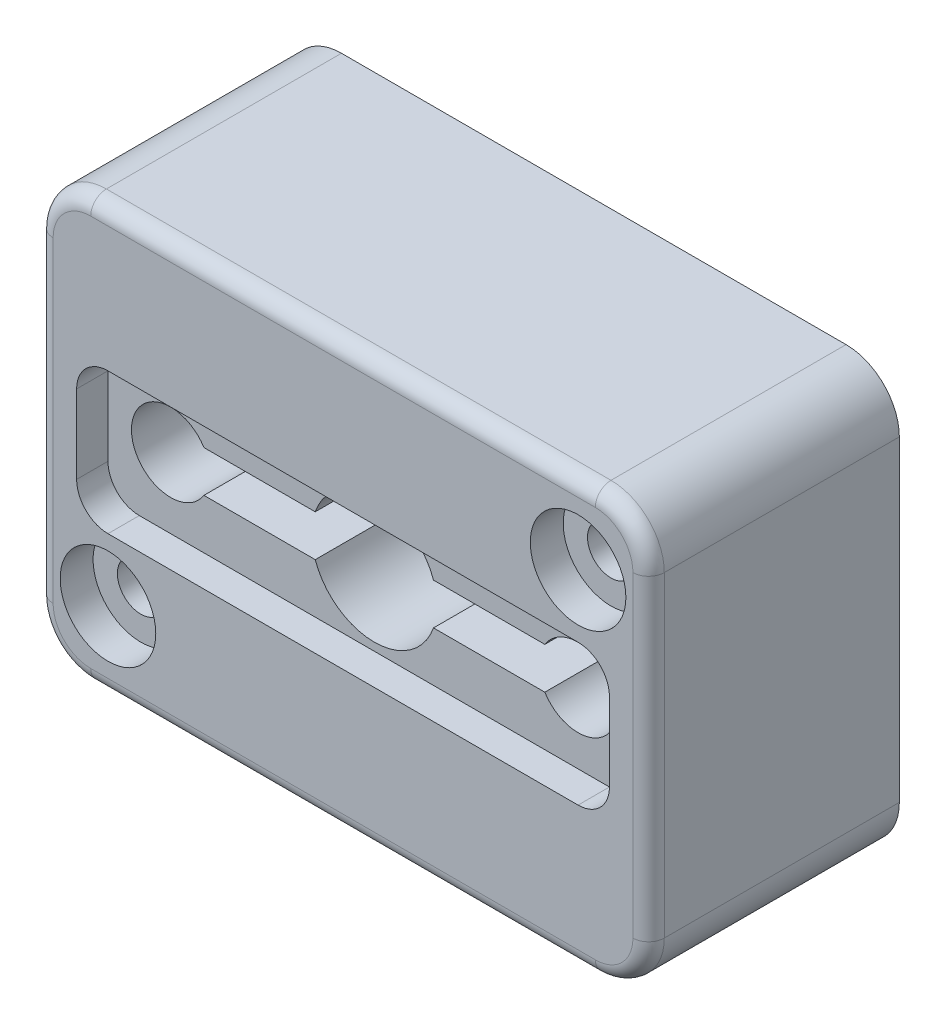
SolidWorks part; units mm, degrees
ref_plane "Ebene vorne" through (0, 0, 0) normal (0, 0, 1) x (1, 0, 0)
ref_plane "Ebene oben" through (0, 0, 0) normal (0, 1, 0) x (1, 0, 0)
ref_plane "Ebene rechts" through (0, 0, 0) normal (1, 0, 0) x (0, 0, -1)
sketch "Skizze1" plane through (0, 0, 0) normal (0, 0, 1) x (1, 0, 0)
  line L0 (0, 0) -> (0, 1.2431) construction
  line L1 (-16.1, 13.5) -> (16.1, 13.5)
  line L2 (-19.5, 10.1) -> (-19.5, -10.1)
  line L3 (-16.1, -13.5) -> (16.1, -13.5)
  line L4 (19.5, 10.1) -> (19.5, -10.1)
  line L5 (0, 0) -> (2.7606, 0) construction
  line L6 (0, 0) -> (-18.5042, 12.5042) construction
  arc A0 (16.1, 13.5) -> (19.5, 10.1) centre (16.1, 10.1) cw
  arc A1 (16.1, -13.5) -> (19.5, -10.1) centre (16.1, -10.1) ccw
  arc A2 (-19.5, -10.1) -> (-16.1, -13.5) centre (-16.1, -10.1) ccw
  arc A3 (-16.1, 13.5) -> (-19.5, 10.1) centre (-16.1, 10.1) ccw
  circle A4 centre (15, 8.5) radius 1.5
  circle A5 centre (-15, -8.5) radius 1.5
  dimension "D3" = 3.4
  dimension "D4" = 3
  dimension "D6" = 3
  dimension "D1" = 13.5
  dimension "D2" = 39
  dimension "D5" = 8.5
  dimension "D7" = 8.5
  dimension "D8" = 15
  dimension "D9" = 15
extrude "Aufsatz-Linear austragen1" add sketch "Skizze1" along normal blind 16
sketch "Skizze2" plane through (0, 0, 16) normal (0, 0, 1) x (1, 0, 0)
  line L0 (0, 0) -> (-26.466, 0) construction
  line L1 (-26.466, 0) -> (23.4019, 0) construction
  line L2 (0, 0) -> (0, 14.7938) construction
  line L4 (-15, 4.5) -> (15, 4.5)
  line L5 (-17, 2.5) -> (-17, -2.5)
  line L6 (-15, -4.5) -> (15, -4.5)
  line L7 (17, 2.5) -> (17, -2.5)
  arc A0 (15, 4.5) -> (17, 2.5) centre (15, 2.5) cw
  arc A1 (15, -4.5) -> (17, -2.5) centre (15, -2.5) ccw
  arc A2 (-17, -2.5) -> (-15, -4.5) centre (-15, -2.5) ccw
  arc A3 (-15, 4.5) -> (-17, 2.5) centre (-15, 2.5) ccw
  point P11 (17, 4.5)
  point P16 (-17, -4.5)
  point P19 (-17, 4.5)
  dimension "D3" = 2
  dimension "D1" = 34
  dimension "D2" = 9
extrude "Schnitt-Linear austragen1" cut sketch "Skizze2" against normal blind 2
sketch "Skizze3" plane through (0, 0, 14) normal (0, 0, 1) x (1, 0, 0)
  line L0 (0, 0) -> (0, 14.7363) construction
  line L1 (0, 0) -> (-23.0189, 0) construction
  line L2 (-23.0189, 0) -> (22.4444, 0) construction
  circle A0 centre (-13, 0) radius 2.5
  circle A1 centre (13, 0) radius 2.5
  dimension "D1" = 5
  dimension "D2" = 26
extrude "Schnitt-Linear austragen2" cut sketch "Skizze3" against normal blind 7
sketch "Skizze4" plane through (0, 0, 16) normal (0, 0, 1) x (1, 0, 0)
  line L0 (13.5, 8.5) -> (16.5, 8.5) construction
  line L1 (15, 10) -> (15, 7) construction
  circle A0 centre (15, 8.5) radius 1.5 construction
  circle A1 centre (15, 8.5) radius 3.05
  circle A2 centre (-15, -8.5) radius 3.05
  point P9 (-15, -8.5)
  dimension "D1" = 6.1
  dimension "D2" = 6.1
extrude "Schnitt-Linear austragen3" cut sketch "Skizze4" against normal blind 2.1
fillet "Verrundung1" radius 1 8 edges at (-18.5042, 12.5042, 16) (-18.5042, -12.5042, 16) (0, -13.5, 16) (18.5042, -12.5042, 16) (18.5042, 12.5042, 16) (19.5, 0, 16) (0, 13.5, 16) (-19.5, 0, 16)
sketch "Skizze5" plane through (0, 0, 14) normal (0, 0, 1) x (1, 0, 0)
  circle A0 centre (0, 0) radius 3.9972
extrude "Schnitt-Linear austragen4" cut sketch "Skizze5" against normal through all
sketch "Skizze6" plane through (0, 0, 14) normal (0, 0, 1) x (1, 0, 0)
  line L0 (0, 0) -> (0, 5.7529) construction
  line L1 (-11.748, 1.3206) -> (11.748, 1.3206)
  line L2 (-11.748, 1.3206) -> (-11.748, -1.3206)
  line L3 (-11.748, -1.3206) -> (11.748, -1.3206)
  line L4 (11.748, 1.3206) -> (11.748, -1.3206)
  line L5 (0, 0) -> (6.8828, 0) construction
extrude "Schnitt-Linear austragen5" cut sketch "Skizze6" against normal blind 4
